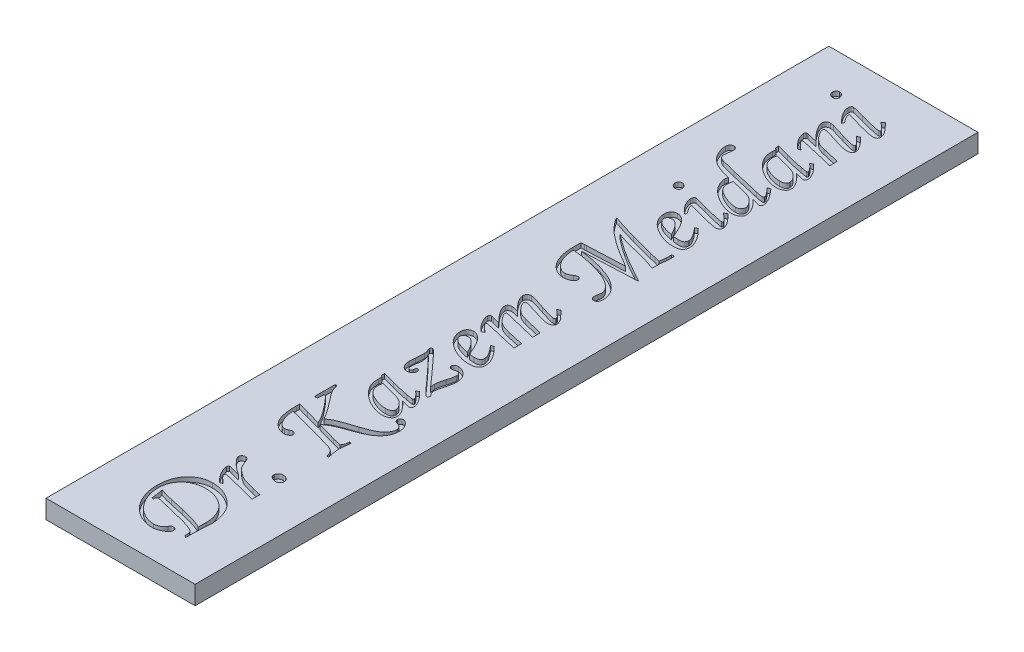
SolidWorks part; units mm, degrees
ref_plane "Front Plane" through (0, 0, 0) normal (0, 0, 1) x (1, 0, 0)
ref_plane "Top Plane" through (0, 0, 0) normal (0, 1, 0) x (1, 0, 0)
ref_plane "Right Plane" through (0, 0, 0) normal (1, 0, 0) x (0, 0, -1)
sketch "Sketch1" plane through (0, 0, 0) normal (0, 0, 1) x (1, 0, 0)
  line L0 (0, 1.5875) -> (0, -1.5875)
  line L1 (-12.7, 0) -> (12.7, 0) construction
  point P6 (0, 0)
  dimension "Width" = 25.4
  dimension "Thk" = 3.175
sketch "Sketch2" plane through (0, 0, 0) normal (1, 0, 0) x (0, 0, -1)
  line L0 (66.675, 0) -> (-66.675, 0)
  point P4 (0, 0)
  dimension "Length" = 133.35
sketch "Sketch3" plane through (0, 0, 0) normal (0, 0, 1) x (1, 0, 0)
  line L1 (12.7, 1.5875) -> (-12.7, 1.5875)
  line L2 (12.7, 1.5875) -> (12.7, -1.5875)
  line L3 (12.7, -1.5875) -> (-12.7, -1.5875)
  line L4 (-12.7, 1.5875) -> (-12.7, -1.5875)
  line L5 (12.7, 1.5875) -> (-12.7, -1.5875) construction
  line L6 (12.7, -1.5875) -> (-12.7, 1.5875) construction
  point P0 (0, 0)
extrude "Boss-Extrude1" add sketch "Sketch3" along normal up to vertex (66.675 mm away) and the other way up to vertex (66.675 mm away) up to point (0, 0, 66.675) other way up to point (0, 0, -66.675)
sketch "Sketch4" plane through (0, 1.5875, 0) normal (0, 1, 0) x (1, 0, 0)
  line L0 (0, 0) -> (5, 0) construction
  line L1 (5, -66.675) -> (5, 66.675) construction
  line L2 (12.7, 66.675) -> (-12.7, 66.675) construction
  text T0 "Dr. Kazem Meidani " font "Monotype Corsiva" height 10
  point P8 (5, 0)
  dimension "D1" = 5
extrude "Cut-Extrude1" cut sketch "Sketch4" against normal blind 0.7937
